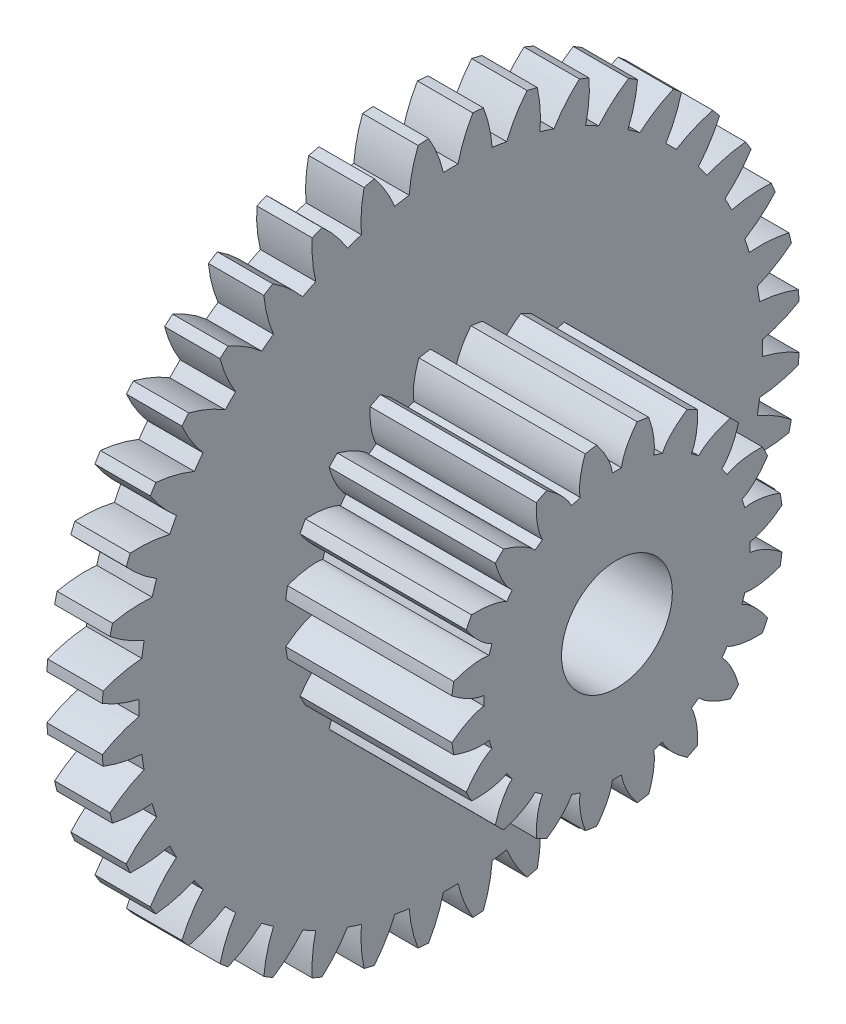
SolidWorks part; units mm, degrees
ref_plane "Plane1" through (0, 0, 0) normal (0, 0, 1) x (1, 0, 0)
ref_plane "Plane2" through (0, 0, 0) normal (0, 1, 0) x (1, 0, 0)
ref_plane "Plane3" through (0, 0, 0) normal (1, 0, 0) x (0, 0, -1)
sketch "HoldingSke" plane through (0, 0, 0) normal (0, 1, 0) x (1, 0, 0)
  line L0 (0, 0) -> (2.5535, -2.1426)
  line L1 (-15, 0) -> (100, 0) construction
  line L2 (0, 0) -> (-2.1039, 2.3779)
  line L3 (0, 0) -> (-11.863, 4.5341)
  line L4 (0, 0) -> (6.6156, 5.5511)
  line L5 (0, 0) -> (-46.8476, -17.4728)
  line L6 (0, 0) -> (-0.829, -0.5593)
  line L7 (-2.1039, 2.3779) -> (8.6586, 51.2059)
  line L8 (-76.2, 54.61) -> (-75.9, 54.61)
  line L9 (-71.009, 38.7566) -> (-53.1078, 45.2721)
  line L10 (-76.2, 71.12) -> (104.1128, 71.12)
  line L11 (0, 0) -> (-1, 0)
  line L12 (-76.2, 101.6) -> (-76.19, 101.6)
  line L13 (24.9733, 27.94) -> (52.9518, 28.4284)
  line L14 (24.9733, 27.94) -> (24.9743, 27.94)
  line L15 (24.9733, 27.94) -> (100.4006, 29.5858)
  line L16 (-63.627, -0.3) -> (-12.827, -0.3)
  circle A0 centre (0, 0) radius 1
  circle A1 centre (0, 0) radius 5.624
  circle A2 centre (0, 0) radius 37.5
  circle A3 centre (0, 0) radius 1
  dimension "MHD" = 11.248
  dimension "Hub_dia" = 75
  dimension "Bore" = 2
  dimension "MBD" = 2
  dimension "Num_teeth" = 40
  dimension "Pitch" = 3.3333
  dimension "Overall_len" = 50
  dimension "Show_teeth" = 40
  dimension "Thickness" = 1
  dimension "OAL" = 50.0001
  dimension "T_dim" = 0.3
  dimension "Ap" = 20
  dimension "H" = 19.05
  dimension "Pitch_radius" = 180.3128
  dimension "Width" = 1
  dimension "Backlash" = 0.01
  dimension "Addendum_fac" = 1
  dimension "Dedendum_fac" = 1.25
  dimension "Clearance_fac" = 0.25
  dimension "Dedendum_add" = 0.001
  dimension "Module" = 0.3
sketch "BasProSke" plane through (0, 0, 0) normal (0, 1, 0) x (1, 0, 0)
  line L0 (-10, 0) -> (60, 0) construction
  line L1 (0, 0) -> (0, 6.3)
  line L2 (0, 0) -> (1, 0)
  line L3 (1, 0) -> (1, 6.3)
  line L4 (1, 6.3) -> (0, 6.3)
  dimension "Thickness" = 1
  dimension "Diameter" = 12.6
revolve "Base-Revolve" add sketch "BasProSke" angle 360 about L0
sketch "TooCutSke" plane through (0, 0, 0) normal (1, 0, 0) x (0, 0, -1)
  line L1 (0, 0) -> (0, 107) construction
  line L2 (0, 0) -> (-0.2531, 5.9947) construction
  line L3 (0, 0) -> (-0.9409, 11.9551) construction
  line L4 (-0.2531, 5.9947) -> (-0.4704, 5.9776) construction
  arc A0 (0.1321, 5.6224) -> (-0.1321, 5.6224) centre (0, 0) ccw
  arc A1 (0.4141, 6.3118) -> (-0.4141, 6.3118) centre (0, 0) ccw
  circle A2 centre (0, 0) radius 6 construction
  circle A3 centre (0, 0) radius 5.6382 construction
  arc A4 (-0.1321, 5.6224) -> (-0.4141, 6.3118) centre (-2.4676, 5.0695) ccw
  arc A5 (0.4141, 6.3118) -> (0.1321, 5.6224) centre (2.4676, 5.0695) ccw
  dimension "Root_dia" = 11.248
  dimension "Overcut_dia" = 12.6508
  dimension "Pitch_dia" = 12
  dimension "Base_dia" = 11.2763
  dimension "Flank_rad" = 2.4
  dimension "Half_ang" = 4.5
  dimension "Half_CT" = 0.2181
extrude "ToothCut" cut sketch "TooCutSke" along normal through all
fillet "Breaks" [suppressed] radius 0.006
fillet "RootFillets" [suppressed] radius 0.076
pattern_circular "TeethCuts" count 40 every 9 about axis through (-10, 0, 0) along (1, 0, 0) of "ToothCut", "RootFillets", "Breaks"
sketch "HubNeaOneSke" plane through (0, 0, 0) normal (-1, 0, 0) x (0, 0, 1)
  circle A0 centre (0, 0) radius 5.624
  dimension "Diameter" = 11.248
extrude "HubNearOne" [suppressed] add sketch "HubNeaOneSke" along normal blind 49.0001
sketch "HubNeaBotSke" plane through (0, 0, 0) normal (-1, 0, 0) x (0, 0, 1)
  circle A0 centre (0, 0) radius 5.624
  dimension "Diameter" = 11.248
extrude "HubNearBoth" [suppressed] add sketch "HubNeaBotSke" along normal blind 24.5
ref_plane "FarPln" through (1, 0, 0) normal (1, 0, 0) x (0, 0, -1)
sketch "HubFarSke" plane through (1, 0, 0) normal (1, 0, 0) x (0, 0, -1)
  circle A0 centre (0, 0) radius 5.624
  dimension "Diameter" = 11.248
extrude "HubFar" [suppressed] add sketch "HubFarSke" along normal blind 24.5
sketch "BorSke" plane through (0, 0, 0) normal (1, 0, 0) x (0, 0, -1)
  circle A0 centre (0, 0) radius 1
  dimension "Diameter" = 2
extrude "Bore" cut sketch "BorSke" along normal mid plane 100.0001
sketch "KeySke" plane through (0, 0, 0) normal (1, 0, 0) x (0, 0, -1)
  line L0 (-0.4, 0) -> (-0.4, 1.3)
  line L1 (-0.4, 1.3) -> (0.4, 1.3)
  line L2 (0.4, 1.3) -> (0.4, 0)
  line L3 (0, 0) -> (0, 34) construction
  line L4 (-0.4, 0) -> (0.4, 0)
  dimension "Offset" = 1.3
  dimension "Width" = 0.8
extrude "Keyway" [suppressed] cut sketch "KeySke" along normal mid plane 100.0001
pattern_circular "Keyway2" [suppressed] count 2 every 90 about axis through (-10, 0, 0) along (1, 0, 0)
sketch "Schizzo1" plane through (1, 0, 0) normal (1, 0, 0) x (0, 0, -1)
  circle A0 centre (0, 0) radius 1
  circle A1 centre (0, 0) radius 3
  circle A2 centre (0, 0) radius 1 construction
  dimension "D1" = 6
extrude "Estrusione-Estrusione1" add sketch "Schizzo1" along normal blind 3
sketch "Schizzo2" plane through (4, 0, 0) normal (1, 0, 0) x (0, 0, -1)
  line L0 (0, 0) -> (4.382, 0) construction
  line L1 (4.382, 0) -> (0, 0) construction
  line L2 (0, 0) -> (2.3985, 0.0838) construction
  line L3 (0, 0) -> (2.3985, -0.0838) construction
  line L4 (3.606, -1.1265) -> (3.606, 1.1265)
  arc A0 (2.3985, -0.0838) -> (2.3985, 0.0838) centre (0, 0) ccw
  spline S0 degree 4 poles (2.3985, 0.0838) (2.401, 0.0838) (2.4078, 0.0842) (2.4206, 0.0857) (2.4415, 0.0889) (2.4799, 0.0969) (2.5254, 0.1098) (2.5759, 0.1275) (2.6292, 0.1497) (2.6742, 0.1705) (2.7183, 0.193) (2.7616, 0.217) (2.8132, 0.2479) (2.8739, 0.2874) (2.9429, 0.3371) (3.0187, 0.3975) (3.0933, 0.4634) (3.1643, 0.5316) (3.2331, 0.6042) (3.2977, 0.6771) (3.3615, 0.7565) (3.4188, 0.8316) (3.4793, 0.9194) (3.527, 0.9915) (3.5859, 1.0902) (3.6193, 1.1497) (3.657, 1.2204) (3.673, 1.2525) (3.6829, 1.2722) knots 0 0 0 0 0 0.005377 0.015084 0.028532 0.04661 0.092111 0.119476 0.146842 0.174209 0.201575 0.228941 0.256307 0.307035 0.361767 0.4165 0.471232 0.525964 0.580697 0.635429 0.690161 0.744894 0.799626 0.854358 0.909091 0.954545 1 1 1 1 1 construction
  spline S1 degree 4 poles (2.3985, 0.0838) (2.401, 0.0838) (2.4078, 0.0842) (2.4206, 0.0857) (2.4415, 0.0889) (2.4799, 0.0969) (2.5254, 0.1098) (2.5759, 0.1275) (2.6292, 0.1497) (2.6742, 0.1705) (2.7183, 0.193) (2.7616, 0.217) (2.8132, 0.2479) (2.8739, 0.2874) (2.9429, 0.3371) (3.0187, 0.3975) (3.0933, 0.4634) (3.1643, 0.5316) (3.2331, 0.6042) (3.2977, 0.6771) (3.3615, 0.7565) (3.4188, 0.8316) (3.4793, 0.9194) (3.527, 0.9915) (3.5731, 1.0688) (3.595, 1.1069) (3.606, 1.1265) knots 0 0 0 0 0 0.005377 0.015084 0.028532 0.04661 0.092111 0.119476 0.146842 0.174209 0.201575 0.228941 0.256307 0.307035 0.361767 0.4165 0.471232 0.525964 0.580697 0.635429 0.690161 0.744894 0.799626 0.854358 0.909091 0.909091 0.909091 0.909091 0.909091
  spline S2 degree 4 poles (2.3985, -0.0838) (2.401, -0.0838) (2.4078, -0.0842) (2.4206, -0.0857) (2.4415, -0.0889) (2.4799, -0.0969) (2.5254, -0.1098) (2.5759, -0.1275) (2.6292, -0.1497) (2.6742, -0.1705) (2.7183, -0.193) (2.7616, -0.217) (2.8132, -0.2479) (2.8739, -0.2874) (2.9429, -0.3371) (3.0187, -0.3975) (3.0933, -0.4634) (3.1643, -0.5316) (3.2331, -0.6042) (3.2977, -0.6771) (3.3615, -0.7565) (3.4188, -0.8316) (3.4793, -0.9194) (3.527, -0.9915) (3.5731, -1.0688) (3.595, -1.1069) (3.606, -1.1265) knots 0 0 0 0 0 0.005377 0.015084 0.028532 0.04661 0.092111 0.119476 0.146842 0.174209 0.201575 0.228941 0.256307 0.307035 0.361767 0.4165 0.471232 0.525964 0.580697 0.635429 0.690161 0.744894 0.799626 0.854358 0.909091 0.909091 0.909091 0.909091 0.909091
  dimension "D1" = 4.8
  dimension "D2" = 2
  dimension "D3" = 178
extrude "Taglio-Estrusione1" cut sketch "Schizzo2" against normal up to surface (3 mm away) up to face at (1, 0, 0)
pattern_circular "RipetizioneCircolare1" count 20 over 360 about axis through (4, 0, 0) along (1, 0, 0) of "Taglio-Estrusione1"
equation "' \"Module@HoldingSke\" = 6.35"
equation "' \"Num_teeth@HoldingSke\" = 12"
equation "' \"Ap@HoldingSke\" =  20"
equation "' \"Ap@HoldingSke\" = 20"
equation "' \"Width@HoldingSke\" = 0.5 * 25.4"
equation "' \"Hub_dia@HoldingSke\"= 1 * 25.4"
equation "' \"Hub_dia@HoldingSke\" = 1 * 25.4"
equation "' \"Overall_len@HoldingSke\" = 1.0 * 25.4"
equation "' \"Bore@HoldingSke\" = 0.75 * 25.4"
equation "' \"T_dim@HoldingSke\" = 0.1 * 25.4"
equation "' \"Width@KeySke\" = 0.25 * 25.4"
equation "' \"Show_teeth@HoldingSke\" = 13"
equation "' \"Backlash@HoldingSke\" = 0.009 * 25.4"
equation "' \"Addendum_fac@HoldingSke\" = 1.0"
equation "' \"Dedendum_fac@HoldingSke\" = 1.25"
equation "' \"Dedendum_add@HoldingSke\" = 0.00005 * 25.4"
equation "' \"Clearance_fac@HoldingSke\" = 0.25"
equation "\"Pitch@HoldingSke\" = 1 / \"Module@HoldingSke\""
equation "\"Overcut_dia@TooCutSke\" = (\"Num_teeth@HoldingSke\" + 2 * \"Addendum_fac@HoldingSke\") / \"Pitch@HoldingSke\" + 0.002 * 25.4"
equation "\"Pitch_dia@TooCutSke\" = \"Num_teeth@HoldingSke\" / \"Pitch@HoldingSke\""
equation "\"Base_dia@TooCutSke\" = \"Num_teeth@HoldingSke\" / \"Pitch@HoldingSke\" * cos((\"Ap@HoldingSke\"  * 3.14159265 / 180))"
equation "\"Root_dia@TooCutSke\" = (\"Num_teeth@HoldingSke\" + 2) / \"Pitch@HoldingSke\" - 2 * (\"Addendum_fac@HoldingSke\" + \"Dedendum_fac@HoldingSke\") / \"Pitch@HoldingSke\" - \"Dedendum_add@HoldingSke\" * 2"
equation "\"Half_ang@TooCutSke\" = 180 / \"Num_teeth@HoldingSke\""
equation "\"Half_CT@TooCutSke\" = \"Num_teeth@HoldingSke\" / \"Pitch@HoldingSke\" * sin((3.14159265 / 2 / \"Num_teeth@HoldingSke\")) / 2 - 7 * \"Backlash@HoldingSke\" / 4"
equation "\"Flank_rad@TooCutSke\" = \"Num_teeth@HoldingSke\" / \"Pitch@HoldingSke\" / 5"
equation "\"Radius@RootFillets\" = \"Clearance_fac@HoldingSke\" / \"Pitch@HoldingSke\" + \"Dedendum_add@HoldingSke\""
equation "\"Break_rad@Breaks\" = 0.02 / \"Pitch@HoldingSke\""
equation "\"Thickness@HoldingSke\" = \"Width@HoldingSke\""
equation "\"OAL@HoldingSke\" = \"Thickness@HoldingSke\""
equation "\"MHD@HoldingSke\" = (\"Num_teeth@HoldingSke\" + 2) / \"Pitch@HoldingSke\" - 2 * (\"Addendum_fac@HoldingSke\" + \"Dedendum_fac@HoldingSke\")  / \"Pitch@HoldingSke\" - \"Dedendum_add@HoldingSke\" * 2"
equation "\"MBD@HoldingSke\" = (\"Num_teeth@HoldingSke\" + 2) / \"Pitch@HoldingSke\" - 2 * (\"Addendum_fac@HoldingSke\" + \"Dedendum_fac@HoldingSke\")  / \"Pitch@HoldingSke\" - \"Dedendum_add@HoldingSke\" * 2 - 0.002 * 25.4"
equation "\"MHD@HoldingSke\" = ((sgn( \"MHD@HoldingSke\" - \"Hub_dia@HoldingSke\" )-1)*( \"MHD@HoldingSke\" - \"Hub_dia@HoldingSke\" ))/-2+ \"Hub_dia@HoldingSke\""
equation "\"MBD@HoldingSke\" = ((sgn( \"MBD@HoldingSke\" - \"Bore@HoldingSke\" )-1)*( \"MBD@HoldingSke\" - \"Bore@HoldingSke\" ))/-2+ \"Bore@HoldingSke\""
equation "\"OAL@HoldingSke\" = ((sgn( \"OAL@HoldingSke\" - \"Overall_len@HoldingSke\" )+1)*( \"OAL@HoldingSke\" - \"Overall_len@HoldingSke\" ))/2 + \"Overall_len@HoldingSke\" + 0.000002 * 25.4"
equation "\"Num_teeth@TeethCuts\" = int( \"Show_teeth@HoldingSke\" ) + 1"
equation "\"Num_teeth@TeethCuts\" = ((sgn( \"Num_teeth@TeethCuts\" - \"Num_teeth@HoldingSke\" )-1)*( \"Num_teeth@TeethCuts\" - \"Num_teeth@HoldingSke\" ))/-2+ \"Num_teeth@HoldingSke\""
equation "\"Num_teeth@TeethCuts\" = ((sgn( \"Num_teeth@TeethCuts\" - 2.0)+1)*( \"Num_teeth@TeethCuts\" - 2.0))/2 +2.0"
equation "\"Angle@TeethCuts\" = 360.0 / \"Num_teeth@HoldingSke\""
equation "\"Diameter@BasProSke\" = (\"Num_teeth@HoldingSke\" + 2 * \"Addendum_fac@HoldingSke\") / \"Pitch@HoldingSke\""
equation "\"Thickness@BasProSke\"  = \"Thickness@HoldingSke\""
equation "' \"Fillet_rad@BasProSke\" =  \"Thickness@HoldingSke\" * 0.05"
equation "' \"Fillet_rad@BasProSke\" = \"Thickness@HoldingSke\" * 0.05"
equation "\"MHD@HoldingSke\" = ((sgn( \"MHD@HoldingSke\" - \"Root_dia@TooCutSke\" )-1)*( \"MHD@HoldingSke\" - \"Root_dia@TooCutSke\" ))/-2+ \"Root_dia@TooCutSke\""
equation "\"Diameter@HubNeaOneSke\" = \"MHD@HoldingSke\""
equation "\"Length@HubNearOne\" = \"OAL@HoldingSke\" - \"Thickness@BasProSke\""
equation "\"Diameter@HubNeaBotSke\" = \"MHD@HoldingSke\""
equation "\"Length@HubNearBoth\" = ( \"OAL@HoldingSke\" - \"Thickness@BasProSke\" ) / 2.0"
equation "\"Thickness@FarPln\" = \"Thickness@BasProSke\""
equation "\"Diameter@HubFarSke\" = \"MHD@HoldingSke\""
equation "\"Length@HubFar\" = ( \"OAL@HoldingSke\" - \"Thickness@BasProSke\" ) / 2.0"
equation "\"Diameter@BorSke\" = \"MBD@HoldingSke\""
equation "\"D1@Bore\" = \"OAL@HoldingSke\" * 2.0"
equation "\"D1@Keyway\" = \"OAL@HoldingSke\" * 2.0"
equation "\"Offset@KeySke\" = \"T_dim@HoldingSke\" + \"MBD@HoldingSke\" / 2.0"
